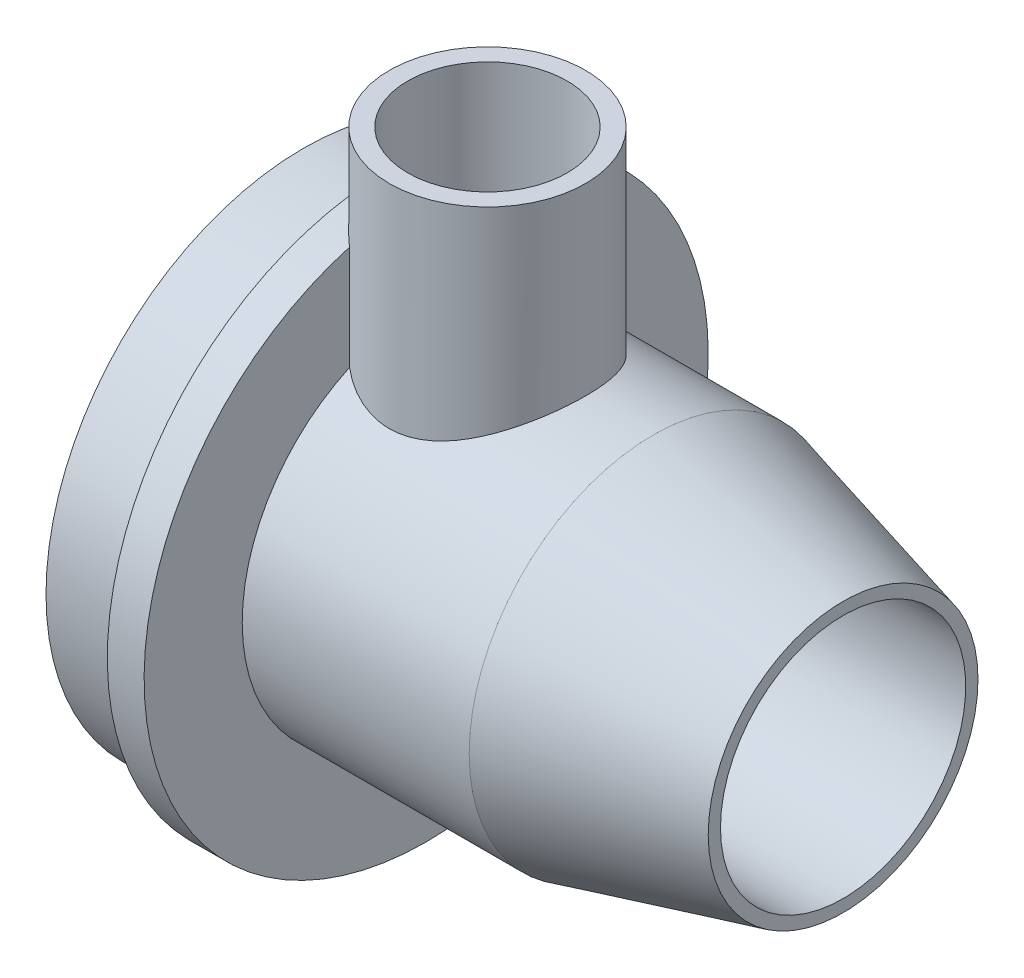
SolidWorks part; units mm, degrees
ref_plane "Plan de face" through (0, 0, 0) normal (0, 0, 1) x (1, 0, 0)
ref_plane "Plan de dessus" through (0, 0, 0) normal (0, 1, 0) x (1, 0, 0)
ref_plane "Plan de droite" through (0, 0, 0) normal (1, 0, 0) x (0, 0, -1)
sketch "Esquisse1" plane through (0, 0, 0) normal (0, 0, 1) x (1, 0, 0)
  line L0 (0, 0) -> (44, 0) construction
  line L1 (44, 0) -> (44, 10) construction
  line L2 (44, 10) -> (44, 11)
  line L3 (44, 10) -> (0, 10)
  line L4 (0, 10) -> (0, 21)
  line L5 (0, 21) -> (7, 21)
  line L6 (7, 21) -> (7, 23)
  line L7 (7, 23) -> (10, 23)
  line L8 (10, 23) -> (10, 15)
  line L9 (10, 15) -> (28.5081, 15)
  line L10 (28.5081, 15) -> (44, 11)
  line L11 (10, 15) -> (10, 10) construction
  dimension "D1" = 44
  dimension "D2" = 10
  dimension "D3" = 1
  dimension "D4" = 11
  dimension "D5" = 7
  dimension "D6" = 3
  dimension "D7" = 16
  dimension "D8" = 5
  dimension "D9" = 2
revolve "Révolution1" add sketch "Esquisse1" angle 360 about L0
ref_plane "Plan1" through (0, 30, 0) normal (0, 1, 0) x (1, 0, 0)
sketch "Esquisse2" plane through (0, 30, 0) normal (0, 1, 0) x (1, 0, 0)
  line L0 (0, 0) -> (15, 0) construction
  circle A0 centre (15, 0) radius 8
  dimension "D2" = 16
  dimension "D1" = 15
extrude "Boss.-Extru.1" add sketch "Esquisse2" against normal up to body separate body
sketch "Esquisse4" plane through (0, 30, 0) normal (0, 1, 0) x (1, 0, 0)
  line L0 (0, 0) -> (15, 0) construction
  circle A0 centre (15, 0) radius 6.5
  dimension "D2" = 13
  dimension "D1" = 15
extrude "Enlèv. mat.-Extru.1" cut sketch "Esquisse4" against normal up to surface (22.4007 mm away)
